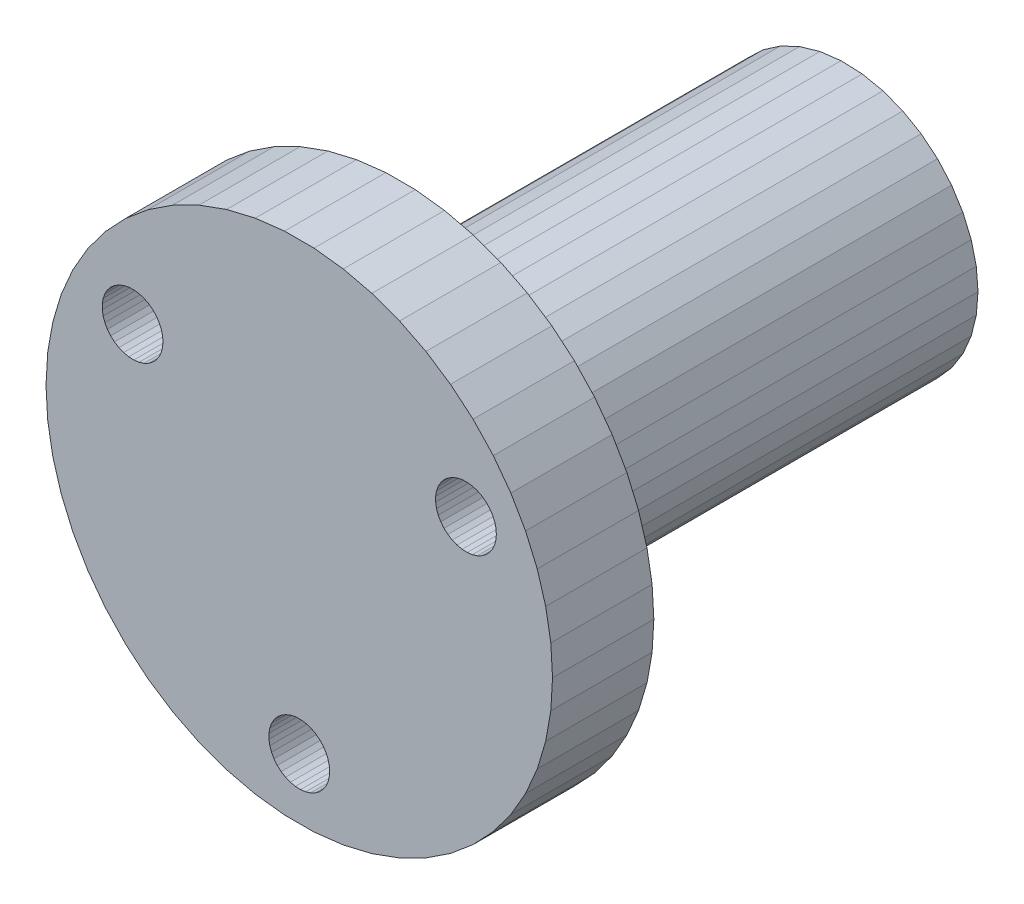
SolidWorks part; units mm, degrees
ref_plane "Front Plane" through (0, 0, 0) normal (0, 0, 1) x (1, 0, 0)
ref_plane "Top Plane" through (0, 0, 0) normal (0, 1, 0) x (1, 0, 0)
ref_plane "Right Plane" through (0, 0, 0) normal (1, 0, 0) x (0, 0, -1)
ref_plane "Plane1" through (0, 0, 22) normal (0, 0, -1) x (-1, 0, 0)
sketch "Sketch1" plane through (0, 0, 22) normal (0, 0, -1) x (-1, 0, 0)
  line L0 (-0.3369, 9.6173) -> (-0.0845, 11.0488)
  line L1 (-0.0845, 11.0488) -> (0, 12.5)
  line L2 (0, 12.5) -> (-0.0845, 13.9512)
  line L3 (-0.0845, 13.9512) -> (-0.3369, 15.3827)
  line L4 (-0.3369, 15.3827) -> (-0.7538, 16.7753)
  line L5 (-0.7538, 16.7753) -> (-1.3296, 18.11)
  line L6 (-1.3296, 18.11) -> (-2.0564, 19.3689)
  line L7 (-2.0564, 19.3689) -> (-2.9244, 20.5348)
  line L8 (-2.9244, 20.5348) -> (-3.922, 21.5922)
  line L9 (-3.922, 21.5922) -> (-5.0355, 22.5265)
  line L10 (-5.0355, 22.5265) -> (-6.25, 23.3253)
  line L11 (-6.25, 23.3253) -> (-7.549, 23.9777)
  line L12 (-7.549, 23.9777) -> (-8.915, 24.4749)
  line L13 (-8.915, 24.4749) -> (-10.3294, 24.8101)
  line L14 (-10.3294, 24.8101) -> (-11.7732, 24.9789)
  line L15 (-11.7732, 24.9789) -> (-13.2268, 24.9789)
  line L16 (-13.2268, 24.9789) -> (-14.6706, 24.8101)
  line L17 (-14.6706, 24.8101) -> (-16.085, 24.4749)
  line L18 (-16.085, 24.4749) -> (-17.451, 23.9777)
  line L19 (-17.451, 23.9777) -> (-18.75, 23.3253)
  line L20 (-18.75, 23.3253) -> (-19.9645, 22.5265)
  line L21 (-19.9645, 22.5265) -> (-21.078, 21.5922)
  line L22 (-21.078, 21.5922) -> (-22.0756, 20.5348)
  line L23 (-22.0756, 20.5348) -> (-22.9436, 19.3689)
  line L24 (-22.9436, 19.3689) -> (-23.6704, 18.11)
  line L25 (-23.6704, 18.11) -> (-24.2462, 16.7753)
  line L26 (-24.2462, 16.7753) -> (-24.6631, 15.3827)
  line L27 (-24.6631, 15.3827) -> (-24.9155, 13.9512)
  line L28 (-24.9155, 13.9512) -> (-25, 12.5)
  line L29 (-25, 12.5) -> (-24.9155, 11.0488)
  line L30 (-24.9155, 11.0488) -> (-24.6631, 9.6173)
  line L31 (-24.6631, 9.6173) -> (-24.2462, 8.2247)
  line L32 (-24.2462, 8.2247) -> (-23.6704, 6.89)
  line L33 (-23.6704, 6.89) -> (-22.9436, 5.6311)
  line L34 (-22.9436, 5.6311) -> (-22.0756, 4.4652)
  line L35 (-22.0756, 4.4652) -> (-21.078, 3.4078)
  line L36 (-21.078, 3.4078) -> (-19.9645, 2.4735)
  line L37 (-19.9645, 2.4735) -> (-18.75, 1.6747)
  line L38 (-18.75, 1.6747) -> (-17.451, 1.0223)
  line L39 (-17.451, 1.0223) -> (-16.085, 0.5251)
  line L40 (-16.085, 0.5251) -> (-14.6706, 0.1899)
  line L41 (-14.6706, 0.1899) -> (-13.2268, 0.0211)
  line L42 (-13.2268, 0.0211) -> (-11.7732, 0.0211)
  line L43 (-11.7732, 0.0211) -> (-10.3294, 0.1899)
  line L44 (-10.3294, 0.1899) -> (-8.915, 0.5251)
  line L45 (-8.915, 0.5251) -> (-7.549, 1.0223)
  line L46 (-7.549, 1.0223) -> (-6.25, 1.6747)
  line L47 (-6.25, 1.6747) -> (-5.0355, 2.4735)
  line L48 (-5.0355, 2.4735) -> (-3.922, 3.4078)
  line L49 (-3.922, 3.4078) -> (-2.9244, 4.4652)
  line L50 (-2.9244, 4.4652) -> (-2.0564, 5.6311)
  line L51 (-2.0564, 5.6311) -> (-1.3296, 6.89)
  line L52 (-1.3296, 6.89) -> (-0.7538, 8.2247)
  line L53 (-0.7538, 8.2247) -> (-0.3369, 9.6173)
extrude "Boss-Extrude1" add sketch "Sketch1" against normal blind 5
sketch "Sketch2" plane through (0, 0, 22) normal (0, 0, -1) x (-1, 0, 0)
  line L0 (-5.7512, 16.9965) -> (-5.6871, 16.7503)
  line L1 (-5.6871, 16.7503) -> (-5.5823, 16.5185)
  line L2 (-5.5823, 16.5185) -> (-5.4398, 16.3077)
  line L3 (-5.4398, 16.3077) -> (-5.2638, 16.124)
  line L4 (-5.2638, 16.124) -> (-5.0592, 15.9727)
  line L5 (-5.0592, 15.9727) -> (-4.832, 15.8582)
  line L6 (-4.832, 15.8582) -> (-4.5888, 15.7837)
  line L7 (-4.5888, 15.7837) -> (-4.3364, 15.7514)
  line L8 (-4.3364, 15.7514) -> (-4.0822, 15.7622)
  line L9 (-4.0822, 15.7622) -> (-3.8335, 15.8157)
  line L10 (-3.8335, 15.8157) -> (-3.5975, 15.9106)
  line L11 (-3.5975, 15.9106) -> (-3.3808, 16.044)
  line L12 (-3.3808, 16.044) -> (-3.1898, 16.2121)
  line L13 (-3.1898, 16.2121) -> (-3.03, 16.41)
  line L14 (-3.03, 16.41) -> (-2.9059, 16.6321)
  line L15 (-2.9059, 16.6321) -> (-2.8212, 16.872)
  line L16 (-2.8212, 16.872) -> (-2.7782, 17.1228)
  line L17 (-2.7782, 17.1228) -> (-2.7782, 17.3772)
  line L18 (-2.7782, 17.3772) -> (-2.8212, 17.628)
  line L19 (-2.8212, 17.628) -> (-2.9059, 17.8679)
  line L20 (-2.9059, 17.8679) -> (-3.03, 18.09)
  line L21 (-3.03, 18.09) -> (-3.1898, 18.2879)
  line L22 (-3.1898, 18.2879) -> (-3.3808, 18.456)
  line L23 (-3.3808, 18.456) -> (-3.5975, 18.5894)
  line L24 (-3.5975, 18.5894) -> (-3.8335, 18.6842)
  line L25 (-3.8335, 18.6842) -> (-4.0822, 18.7379)
  line L26 (-4.0822, 18.7379) -> (-4.3364, 18.7486)
  line L27 (-4.3364, 18.7486) -> (-4.5888, 18.7163)
  line L28 (-4.5888, 18.7163) -> (-4.832, 18.6418)
  line L29 (-4.832, 18.6418) -> (-5.0592, 18.5273)
  line L30 (-5.0592, 18.5273) -> (-5.2638, 18.376)
  line L31 (-5.2638, 18.376) -> (-5.4398, 18.1923)
  line L32 (-5.4398, 18.1923) -> (-5.5823, 17.9815)
  line L33 (-5.5823, 17.9815) -> (-5.6871, 17.7497)
  line L34 (-5.6871, 17.7497) -> (-5.7512, 17.5035)
  line L35 (-5.7512, 17.5035) -> (-5.7728, 17.25)
  line L36 (-5.7728, 17.25) -> (-5.7512, 16.9965)
extrude "Cut-Extrude1" cut sketch "Sketch2" against normal through all
sketch "Sketch3" plane through (0, 0, 22) normal (0, 0, -1) x (-1, 0, 0)
  line L0 (-13.6671, 3.9423) -> (-13.8095, 3.7315)
  line L1 (-13.8095, 3.7315) -> (-13.9143, 3.4997)
  line L2 (-13.9143, 3.4997) -> (-13.9784, 3.2535)
  line L3 (-13.9784, 3.2535) -> (-14, 3)
  line L4 (-14, 3) -> (-13.9784, 2.7465)
  line L5 (-13.9784, 2.7465) -> (-13.9143, 2.5003)
  line L6 (-13.9143, 2.5003) -> (-13.8095, 2.2685)
  line L7 (-13.8095, 2.2685) -> (-13.6671, 2.0577)
  line L8 (-13.6671, 2.0577) -> (-13.491, 1.874)
  line L9 (-13.491, 1.874) -> (-13.2865, 1.7227)
  line L10 (-13.2865, 1.7227) -> (-13.0593, 1.6082)
  line L11 (-13.0593, 1.6082) -> (-12.816, 1.5337)
  line L12 (-12.816, 1.5337) -> (-12.5637, 1.5014)
  line L13 (-12.5637, 1.5014) -> (-12.3095, 1.5121)
  line L14 (-12.3095, 1.5121) -> (-12.0608, 1.5657)
  line L15 (-12.0608, 1.5657) -> (-11.8247, 1.6606)
  line L16 (-11.8247, 1.6606) -> (-11.6081, 1.794)
  line L17 (-11.6081, 1.794) -> (-11.4171, 1.9621)
  line L18 (-11.4171, 1.9621) -> (-11.2572, 2.16)
  line L19 (-11.2572, 2.16) -> (-11.1332, 2.3821)
  line L20 (-11.1332, 2.3821) -> (-11.0484, 2.622)
  line L21 (-11.0484, 2.622) -> (-11.0054, 2.8728)
  line L22 (-11.0054, 2.8728) -> (-11.0054, 3.1272)
  line L23 (-11.0054, 3.1272) -> (-11.0484, 3.378)
  line L24 (-11.0484, 3.378) -> (-11.1332, 3.6179)
  line L25 (-11.1332, 3.6179) -> (-11.2572, 3.84)
  line L26 (-11.2572, 3.84) -> (-11.4171, 4.0379)
  line L27 (-11.4171, 4.0379) -> (-11.6081, 4.206)
  line L28 (-11.6081, 4.206) -> (-11.8247, 4.3394)
  line L29 (-11.8247, 4.3394) -> (-12.0608, 4.4343)
  line L30 (-12.0608, 4.4343) -> (-12.3095, 4.4879)
  line L31 (-12.3095, 4.4879) -> (-12.5637, 4.4986)
  line L32 (-12.5637, 4.4986) -> (-12.816, 4.4663)
  line L33 (-12.816, 4.4663) -> (-13.0593, 4.3918)
  line L34 (-13.0593, 4.3918) -> (-13.2865, 4.2773)
  line L35 (-13.2865, 4.2773) -> (-13.491, 4.126)
  line L36 (-13.491, 4.126) -> (-13.6671, 3.9423)
extrude "Cut-Extrude2" cut sketch "Sketch3" against normal through all
sketch "Sketch4" plane through (0, 0, 27) normal (0, 0, 1) x (1, 0, 0)
  line L0 (19.4845, 18.09) -> (19.3604, 17.8679)
  line L1 (19.3604, 17.8679) -> (19.2756, 17.628)
  line L2 (19.2756, 17.628) -> (19.2326, 17.3772)
  line L3 (19.2326, 17.3772) -> (19.2326, 17.1228)
  line L4 (19.2326, 17.1228) -> (19.2756, 16.872)
  line L5 (19.2756, 16.872) -> (19.3604, 16.6321)
  line L6 (19.3604, 16.6321) -> (19.4845, 16.41)
  line L7 (19.4845, 16.41) -> (19.6443, 16.2121)
  line L8 (19.6443, 16.2121) -> (19.8353, 16.044)
  line L9 (19.8353, 16.044) -> (20.0519, 15.9106)
  line L10 (20.0519, 15.9106) -> (20.288, 15.8157)
  line L11 (20.288, 15.8157) -> (20.5367, 15.7622)
  line L12 (20.5367, 15.7622) -> (20.7909, 15.7514)
  line L13 (20.7909, 15.7514) -> (21.0433, 15.7837)
  line L14 (21.0433, 15.7837) -> (21.2865, 15.8582)
  line L15 (21.2865, 15.8582) -> (21.5137, 15.9727)
  line L16 (21.5137, 15.9727) -> (21.7183, 16.124)
  line L17 (21.7183, 16.124) -> (21.8943, 16.3077)
  line L18 (21.8943, 16.3077) -> (22.0368, 16.5185)
  line L19 (22.0368, 16.5185) -> (22.1416, 16.7503)
  line L20 (22.1416, 16.7503) -> (22.2057, 16.9965)
  line L21 (22.2057, 16.9965) -> (22.2272, 17.25)
  line L22 (22.2272, 17.25) -> (22.2057, 17.5035)
  line L23 (22.2057, 17.5035) -> (22.1416, 17.7497)
  line L24 (22.1416, 17.7497) -> (22.0368, 17.9815)
  line L25 (22.0368, 17.9815) -> (21.8943, 18.1923)
  line L26 (21.8943, 18.1923) -> (21.7183, 18.376)
  line L27 (21.7183, 18.376) -> (21.5137, 18.5273)
  line L28 (21.5137, 18.5273) -> (21.2865, 18.6418)
  line L29 (21.2865, 18.6418) -> (21.0433, 18.7163)
  line L30 (21.0433, 18.7163) -> (20.7909, 18.7486)
  line L31 (20.7909, 18.7486) -> (20.5367, 18.7379)
  line L32 (20.5367, 18.7379) -> (20.288, 18.6842)
  line L33 (20.288, 18.6842) -> (20.0519, 18.5894)
  line L34 (20.0519, 18.5894) -> (19.8353, 18.456)
  line L35 (19.8353, 18.456) -> (19.6443, 18.2879)
  line L36 (19.6443, 18.2879) -> (19.4845, 18.09)
extrude "Cut-Extrude3" cut sketch "Sketch4" against normal through all
sketch "Sketch5" plane through (0, 0, 22) normal (0, 0, -1) x (-1, 0, 0)
  line L0 (-18.9158, 11.4573) -> (-19, 12.5)
  line L1 (-19, 12.5) -> (-18.9158, 13.5427)
  line L2 (-18.9158, 13.5427) -> (-18.6655, 14.5583)
  line L3 (-18.6655, 14.5583) -> (-18.2555, 15.5207)
  line L4 (-18.2555, 15.5207) -> (-17.6964, 16.4048)
  line L5 (-17.6964, 16.4048) -> (-17.0027, 17.1878)
  line L6 (-17.0027, 17.1878) -> (-16.1924, 17.8494)
  line L7 (-16.1924, 17.8494) -> (-15.2865, 18.3724)
  line L8 (-15.2865, 18.3724) -> (-14.3084, 18.7434)
  line L9 (-14.3084, 18.7434) -> (-13.2835, 18.9526)
  line L10 (-13.2835, 18.9526) -> (-12.2383, 18.9947)
  line L11 (-12.2383, 18.9947) -> (-11.1998, 18.8686)
  line L12 (-11.1998, 18.8686) -> (-10.1951, 18.5776)
  line L13 (-10.1951, 18.5776) -> (-9.25, 18.1292)
  line L14 (-9.25, 18.1292) -> (-8.3891, 17.5349)
  line L15 (-8.3891, 17.5349) -> (-7.6347, 16.8103)
  line L16 (-7.6347, 16.8103) -> (-7.0063, 15.974)
  line L17 (-7.0063, 15.974) -> (-6.5201, 15.0478)
  line L18 (-6.5201, 15.0478) -> (-6.1889, 14.0556)
  line L19 (-6.1889, 14.0556) -> (-6.0211, 13.023)
  line L20 (-6.0211, 13.023) -> (-6, 12.5)
  line L21 (-6, 12.5) -> (-6.0211, 11.977)
  line L22 (-6.0211, 11.977) -> (-6.1889, 10.9444)
  line L23 (-6.1889, 10.9444) -> (-6.5201, 9.9522)
  line L24 (-6.5201, 9.9522) -> (-7.0063, 9.026)
  line L25 (-7.0063, 9.026) -> (-7.6347, 8.1897)
  line L26 (-7.6347, 8.1897) -> (-8.3891, 7.4651)
  line L27 (-8.3891, 7.4651) -> (-9.25, 6.8708)
  line L28 (-9.25, 6.8708) -> (-10.1951, 6.4224)
  line L29 (-10.1951, 6.4224) -> (-11.1998, 6.1314)
  line L30 (-11.1998, 6.1314) -> (-12.2383, 6.0053)
  line L31 (-12.2383, 6.0053) -> (-13.2835, 6.0474)
  line L32 (-13.2835, 6.0474) -> (-14.3084, 6.2566)
  line L33 (-14.3084, 6.2566) -> (-15.2865, 6.6276)
  line L34 (-15.2865, 6.6276) -> (-16.1924, 7.1506)
  line L35 (-16.1924, 7.1506) -> (-17.0027, 7.8122)
  line L36 (-17.0027, 7.8122) -> (-17.6964, 8.5952)
  line L37 (-17.6964, 8.5952) -> (-18.2555, 9.4793)
  line L38 (-18.2555, 9.4793) -> (-18.6655, 10.4417)
  line L39 (-18.6655, 10.4417) -> (-18.9158, 11.4573)
extrude "Boss-Extrude2" add sketch "Sketch5" along normal blind 22
sketch "Sketch6" plane through (0, 0, 0) normal (0, 0, -1) x (-1, 0, 0)
  line L0 (-15.3237, 11.8391) -> (-15.1695, 11.3669)
  line L1 (-15.1695, 11.3669) -> (-14.937, 10.928)
  line L2 (-14.937, 10.928) -> (-14.6329, 10.5352)
  line L3 (-14.6329, 10.5352) -> (-14.2664, 10.2)
  line L4 (-14.2664, 10.2) -> (-10.7336, 10.2)
  line L5 (-10.7336, 10.2) -> (-10.367, 10.5352)
  line L6 (-10.367, 10.5352) -> (-10.063, 10.928)
  line L7 (-10.063, 10.928) -> (-9.8305, 11.3669)
  line L8 (-9.8305, 11.3669) -> (-9.6763, 11.8391)
  line L9 (-9.6763, 11.8391) -> (-9.6049, 12.3307)
  line L10 (-9.6049, 12.3307) -> (-9.6185, 12.8272)
  line L11 (-9.6185, 12.8272) -> (-9.7166, 13.3142)
  line L12 (-9.7166, 13.3142) -> (-9.8964, 13.7772)
  line L13 (-9.8964, 13.7772) -> (-10.1526, 14.2028)
  line L14 (-10.1526, 14.2028) -> (-10.4776, 14.5784)
  line L15 (-10.4776, 14.5784) -> (-10.862, 14.8931)
  line L16 (-10.862, 14.8931) -> (-11.2944, 15.1375)
  line L17 (-11.2944, 15.1375) -> (-11.7622, 15.3046)
  line L18 (-11.7622, 15.3046) -> (-12.2516, 15.3893)
  line L19 (-12.2516, 15.3893) -> (-12.7484, 15.3893)
  line L20 (-12.7484, 15.3893) -> (-13.2378, 15.3046)
  line L21 (-13.2378, 15.3046) -> (-13.7056, 15.1375)
  line L22 (-13.7056, 15.1375) -> (-14.138, 14.8931)
  line L23 (-14.138, 14.8931) -> (-14.5224, 14.5784)
  line L24 (-14.5224, 14.5784) -> (-14.8474, 14.2028)
  line L25 (-14.8474, 14.2028) -> (-15.1036, 13.7772)
  line L26 (-15.1036, 13.7772) -> (-15.2834, 13.3142)
  line L27 (-15.2834, 13.3142) -> (-15.3815, 12.8272)
  line L28 (-15.3815, 12.8272) -> (-15.3951, 12.3307)
  line L29 (-15.3951, 12.3307) -> (-15.3237, 11.8391)
extrude "Cut-Extrude4" cut sketch "Sketch6" against normal blind 22
